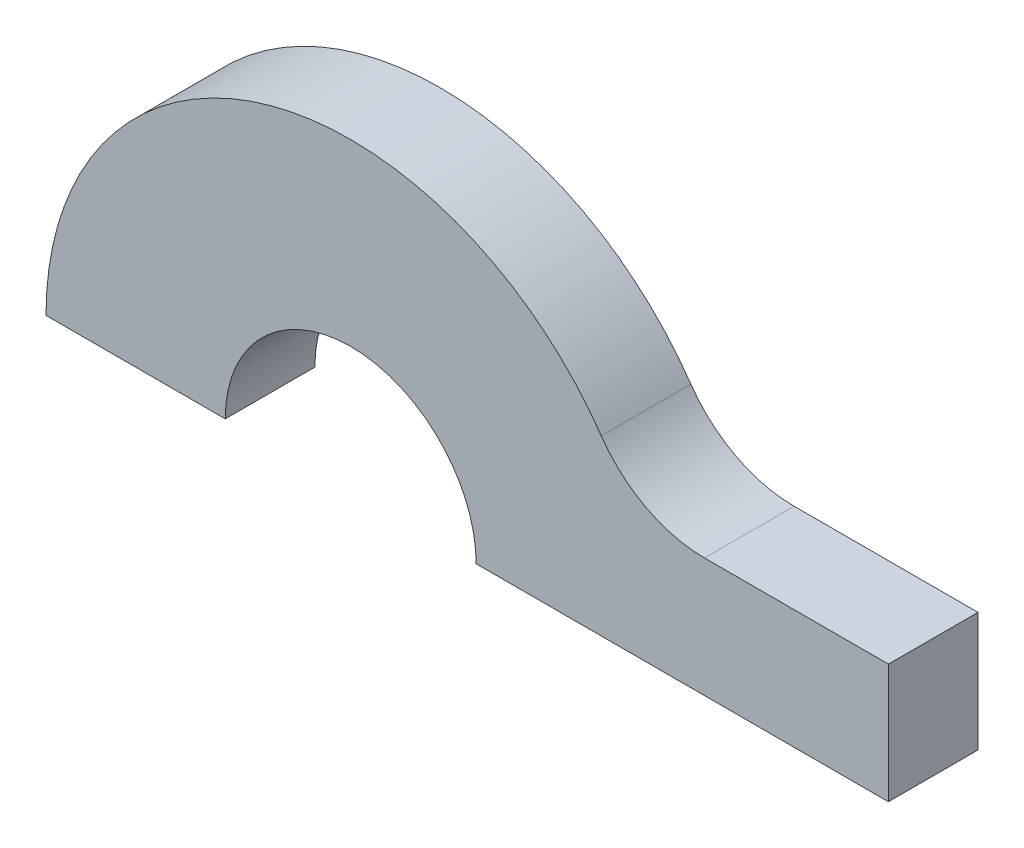
SolidWorks part; units mm, degrees
ref_plane "Plane1" through (0, 0, 0) normal (0, 0, 1) x (1, 0, 0)
ref_plane "Plane2" through (0, 0, 0) normal (0, 1, 0) x (1, 0, 0)
ref_plane "Plane3" through (0, 0, 0) normal (1, 0, 0) x (0, 0, -1)
other "Configuration Table"
sketch "Sketch1" plane through (0, 0, 0) normal (0, 0, 1) x (1, 0, 0)
  line L0 (-76.7748, 0) -> (76.7748, 0) construction
  line L1 (0, 81.4278) -> (0, -89.8032) construction
  line L2 (-43.18, 0) -> (-17.78, 0)
  line L3 (17.78, 0) -> (43.18, 0)
  arc A0 (-17.78, 0) -> (17.78, 0) centre (0, 0) cw
  arc A1 (-43.18, 0) -> (43.18, 0) centre (0, 0) cw
  dimension "D1" = 17.78
  dimension "D2" = 43.18
extrude "Base-Extrude" add sketch "Sketch1" along normal blind 12.7
ref_plane "Plane4" through (50.8, 0, 0) normal (1, 0, 0) x (0, 0, -1)
sketch "Sketch2" plane through (50.8, 0, 0) normal (1, 0, 0) x (0, 0, -1)
  line L0 (-12.7, 0) -> (0, 0) construction
  line L1 (-12.7, 0) -> (0, 0)
  line L2 (-12.7, 0) -> (-12.7, 16.891)
  line L3 (-12.7, 16.891) -> (0, 16.891)
  line L4 (0, 0) -> (0, 17.78) construction
  line L5 (0, 16.891) -> (0, 0)
  dimension "D1" = 16.891
extrude "Boss-Extrude2" add sketch "Sketch2" along normal up to surface (7.62 mm away)
sketch "Sketch3" plane through (50.8, 0, 0) normal (1, 0, 0) x (0, 0, -1)
  line L0 (-12.7, 0) -> (0, 0) construction
  line L1 (-12.7, 0) -> (-12.7, 16.891) construction
  line L2 (-12.7, 16.891) -> (0, 16.891) construction
  line L3 (0, 16.891) -> (0, 0) construction
  line L4 (-12.7, 0) -> (0, 0)
  line L5 (-12.7, 0) -> (-12.7, 16.891)
  line L6 (-12.7, 16.891) -> (0, 16.891)
  line L7 (0, 16.891) -> (0, 0)
extrude "Boss-Extrude3" add sketch "Sketch3" along normal blind 25.4
fillet "Fillet1" radius 17.78 1 edges at (39.7392, 16.891, 6.35)
sketch "Sketch4" plane through (0, 0, 0) normal (0, -1, 0) x (1, 0, 0)
  line L0 (0, -9.1943) -> (0, 32.8553)
split line "Split Line1"
sketch "Sketch5" plane through (0, 0, 12.7) normal (0, 0, 1) x (1, 0, 0)
  line L1 (-32.2445, 28.7194) -> (-32.2445, 52.8674)
  line L2 (-32.2445, 52.8674) -> (31.6653, 52.8674)
  line L3 (31.6653, 52.8674) -> (31.6653, 29.3568)
  arc A1 (35.516, 24.5586) -> (-43.18, 0) centre (0, 0) ccw construction
  spline S0 degree 3 poles (31.6653, 29.3568) (21.1017, 32.6303) (-0.2541, 39.2483) (-21.5052, 32.254) (-32.2445, 28.7194) knots 0 0 0 0 0.49465 1 1 1 1
  point P0 (7.4505, 42.5324)
  point P1 (-11.5266, 37.9376)
  point P3 (-26.4343, 20.9971)
  point P5 (-34.2269, 0)
extrude "Extrude1" [suppressed] cut sketch "Sketch5" against normal through all
